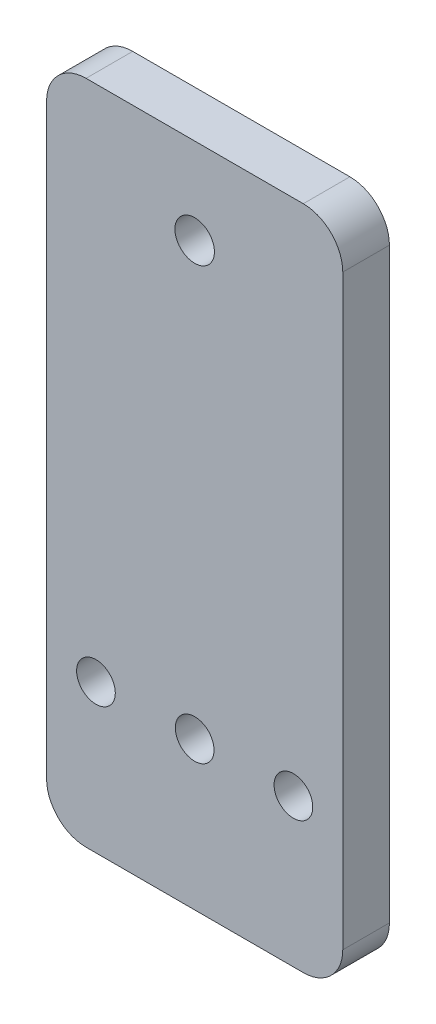
SolidWorks part; units mm, degrees
material "PC High Viscosity"
ref_plane "Front Plane" through (0, 0, 0) normal (0, 0, 1) x (1, 0, 0)
ref_plane "Top Plane" through (0, 0, 0) normal (0, 1, 0) x (1, 0, 0)
ref_plane "Right Plane" through (0, 0, 0) normal (1, 0, 0) x (0, 0, -1)
sketch "Sketch1" plane through (0, 0, 0) normal (0, 0, 1) x (1, 0, 0)
  line L0 (-382.27, -19.05) -> (-354.33, -19.05)
  line L1 (-349.25, -13.97) -> (-349.25, 61.53)
  line L2 (-354.33, 66.61) -> (-382.27, 66.61)
  line L3 (-387.35, 61.53) -> (-387.35, -13.97)
  circle A3 centre (-368.3, 0) radius 2.4892
  circle A4 centre (-355.6, 0) radius 2.4892
  circle A7 centre (-381, 0) radius 2.4892
  arc A9 (-354.33, -19.05) -> (-349.25, -13.97) centre (-354.33, -13.97) ccw
  arc A10 (-387.35, -13.97) -> (-382.27, -19.05) centre (-382.27, -13.97) ccw
  arc A11 (-382.27, 66.61) -> (-387.35, 61.53) centre (-382.27, 61.53) ccw
  arc A12 (-349.25, 61.53) -> (-354.33, 66.61) centre (-354.33, 61.53) ccw
  circle A13 centre (-368.3, 55.53) radius 2.54
  dimension "D6" = 5.08
  dimension "D7" = 11.08
  dimension "D8" = 5.08
  dimension "D9" = 74.58
extrude "Boss-Extrude1" add sketch "Sketch1" along normal blind 6
